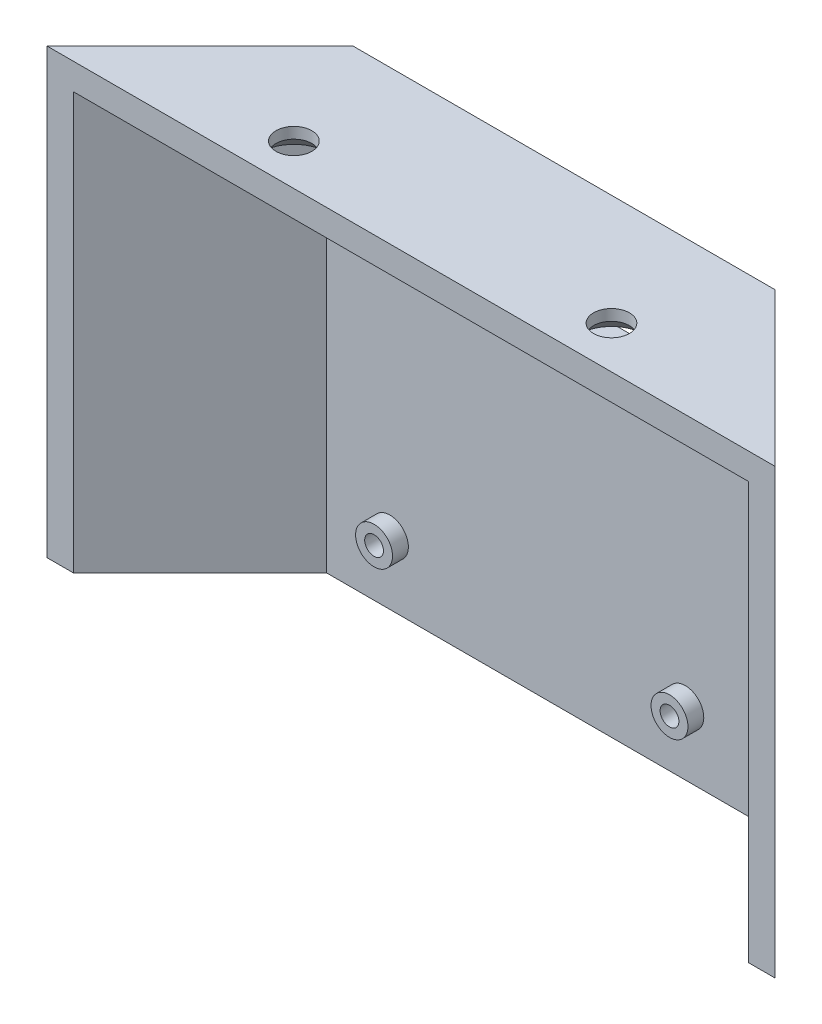
SolidWorks part; units mm, degrees
ref_plane "Front Plane" through (0, 0, 0) normal (0, 0, 1) x (1, 0, 0)
ref_plane "Top Plane" through (0, 0, 0) normal (0, 1, 0) x (1, 0, 0)
ref_plane "Right Plane" through (0, 0, 0) normal (1, 0, 0) x (0, 0, -1)
sketch "Sketch1" plane through (0, 0, 0) normal (0, 1, 0) x (1, 0, 0)
  line L1 (-20, -21) -> (20, -21)
  line L2 (-20, -21) -> (-20, 21)
  line L3 (-20, 21) -> (20, 21)
  line L4 (20, -21) -> (20, 21)
  line L5 (-20, -21) -> (20, 21) construction
  line L6 (-20, 21) -> (20, -21) construction
  point P0 (0, 0)
  dimension "D1" = 40
  dimension "D2" = 42
extrude "Boss-Extrude1" add sketch "Sketch1" along normal blind 2.5
sketch "Sketch2" plane through (0, 2.5, 0) normal (0, 1, 0) x (1, 0, 0)
  line L0 (20, -21) -> (20, 21) construction
  line L1 (-20, 21) -> (20, 21)
  line L2 (-20, 21) -> (-20, 18.5)
  line L3 (-20, 18.5) -> (20, 18.5)
  line L4 (20, 21) -> (20, 18.5)
  dimension "D1" = 2.5
extrude "Boss-Extrude2" add sketch "Sketch2" along normal blind 12
sketch "Sketch3" plane through (0, 2.5, 0) normal (0, 1, 0) x (1, 0, 0)
  line L6 (-14, -15) -> (14, -15) construction
  line L7 (-14, -15) -> (-14, 13) construction
  line L8 (-14, 13) -> (14, 13) construction
  line L9 (14, -15) -> (14, 13) construction
  line L10 (-14, -15) -> (14, 13) construction
  line L11 (-14, 13) -> (14, -15) construction
  line L12 (-20, -21) -> (20, -21) construction
  circle A0 centre (14, 13) radius 1.75
  circle A1 centre (-14, 13) radius 1.75
  circle A2 centre (-14, -15) radius 1.75
  circle A3 centre (14, -15) radius 1.75
  point P1 (0, -1)
  dimension "D4" = 3.5
  dimension "D1" = 6
  dimension "D2" = 28
  dimension "D3" = 28
extrude "Boss-Extrude3" add sketch "Sketch3" along normal blind 1.5
ref_plane "Plane1" through (0, 4, 0) normal (0, 1, 0) x (1, 0, 0)
sketch "Sketch5" plane through (0, 4, 0) normal (0, 1, 0) x (1, 0, 0)
  circle A0 centre (-14, 13) radius 0.89
  circle A1 centre (14, 13) radius 0.89
  circle A2 centre (14, -15) radius 0.89
  circle A3 centre (-14, -15) radius 0.89
  dimension "D1" = 1.78
extrude "Cut-Extrude2" cut sketch "Sketch5" against normal through all
sketch "Sketch6" plane through (0, 4, 0) normal (0, 1, 0) x (1, 0, 0)
  line L1 (2.25, 10.5) -> (12.25, 10.5)
  line L2 (2.25, 10.5) -> (2.25, 15.5)
  line L3 (2.25, 15.5) -> (12.25, 15.5)
  line L4 (12.25, 10.5) -> (12.25, 15.5)
  line L5 (2.25, 10.5) -> (12.25, 15.5) construction
  line L6 (2.25, 15.5) -> (12.25, 10.5) construction
  circle A0 centre (14, 13) radius 1.75 construction
  point P0 (7.25, 13)
  dimension "D1" = 13
  dimension "D2" = 5
  dimension "D3" = 10
extrude "Cut-Extrude3" cut sketch "Sketch6" against normal through all
hole_wizard "CSK for M3 Flat Head Machine Screw1" positions "Sketch7" profile "Sketch8" countersink size "M3" standard "ANSI Metric" end condition through all
sketch "Sketch7" plane through (0, 0, -18.5) normal (0, 0, 1) x (1, 0, 0)
  line L0 (-20, 14.5) -> (-20, 2.5) construction
  line L1 (-20, 14.5) -> (20, 14.5) construction
  point P0 (-15, 10.5983)
  point P2 (14.9998, 10.5)
  dimension "D1" = 30
  dimension "D2" = 5
  dimension "D3" = 4
sketch "Sketch8" plane through (-15, 10.5983, -18.5) normal (1, 0, 0) x (0, -1, 0)
  line L0 (0, 0) -> (0, 2.5)
  line L1 (0, 2.5) -> (1.7, 2.5)
  line L2 (1.7, 2.5) -> (1.7, 1.45)
  line L3 (1.7, 1.45) -> (3.15, 0)
  line L5 (3.15, 0) -> (0, 0)
  line L6 (-1.7, 1.45) -> (-3.15, 0) construction
  line L11 (0, -6.35) -> (0, 107.95) construction
  dimension "Thru Hole Dia." = 3.4
  dimension "Thru Hole Depth" = 2.5
  dimension "Near C'Sink Dia." = 6.3
  dimension "Near C'Sink Angle" = 90
sketch "Sketch9" plane through (0, 0, -21) normal (0, 0, -1) x (-1, 0, 0)
  line L0 (20, 0) -> (34.5, 14.5)
  line L1 (-20, 0) -> (-34.5, 14.5)
  line L3 (-20, 14.5) -> (20, 14.5) construction
  line L4 (-20, 14.5) -> (-20, 0) construction
  line L5 (20, 14.5) -> (20, 0) construction
  line L6 (-34.5, 14.5) -> (-20, 14.5)
  line L7 (20, 14.5) -> (34.5, 14.5)
  line L8 (20, 0) -> (20, 14.5)
  line L9 (-20, 0) -> (-20, 14.5)
  dimension "D1" = 45
  dimension "D2" = 45
extrude "Boss-Extrude4" add sketch "Sketch9" against normal up to surface (2.5 mm away) up to face at (-11.85, 10.5983, -18.5)
sketch "Sketch10" plane through (0, 0, -18.5) normal (0, 0, 1) x (1, 0, 0)
  line L0 (20, 2.5) -> (32, 14.5)
  line L1 (-34.5, 14.5) -> (34.5, 14.5) construction
  line L2 (20, 0) -> (34.5, 14.5) construction
  line L3 (-20, 2.5) -> (-32, 14.5)
  line L4 (-34.5, 14.5) -> (-20, 0) construction
  line L5 (-32, 14.5) -> (-34.5, 14.5)
  line L6 (-34.5, 14.5) -> (-20, 0)
  line L7 (-20, 0) -> (-20, 2.5)
  line L8 (20, 2.5) -> (20, 0)
  line L9 (20, 0) -> (34.5, 14.5)
  line L10 (34.5, 14.5) -> (32, 14.5)
extrude "Boss-Extrude5" add sketch "Sketch10" along normal up to surface (39.5 mm away) up to face at (0, 1.25, 21)
move or copy body "Body-Move/Copy1" bodies to move or copy 109 copy no rotation origin (0, 0, 0) rotation axis (1, 0, 0) rotation angle 90
